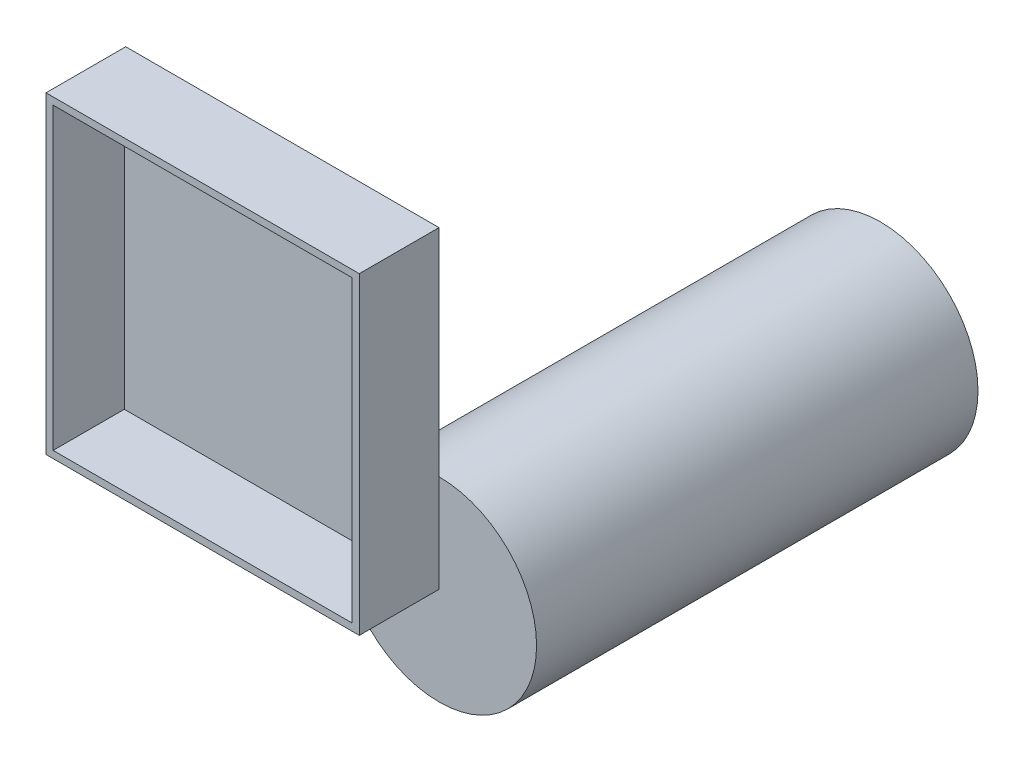
SolidWorks part; units mm, degrees
ref_plane "前基準面" through (0, 0, 0) normal (0, 0, 1) x (1, 0, 0)
ref_plane "上基準面" through (0, 0, 0) normal (0, 1, 0) x (1, 0, 0)
ref_plane "右基準面" through (0, 0, 0) normal (1, 0, 0) x (0, 0, -1)
sketch "草圖1" plane through (0, 0, 0) normal (0, 0, 1) x (1, 0, 0)
  circle A0 centre (0, 0) radius 34.25
  circle A1 centre (0, 0) radius 31.75
  dimension "D1" = 68.5
  dimension "D2" = 63.5
extrude "填料-伸長1" add sketch "草圖1" along normal blind 150
sketch "草圖3" plane through (0, 0, 150) normal (0, 0, 1) x (1, 0, 0)
  circle A0 centre (0, 0) radius 34.25
  dimension "D1" = 68.5
extrude "填料-伸長2" add sketch "草圖3" along normal blind 5
sketch "草圖4" plane through (0, 0, 155) normal (0, 0, 1) x (1, 0, 0)
  line L0 (-55, 110) -> (-55, 51.8909) construction
  line L1 (0, 0) -> (-110, 0)
  line L2 (0, 0) -> (0, 110)
  line L3 (0, 110) -> (-110, 110)
  line L4 (-110, 0) -> (-110, 110)
  dimension "D1" = 110
  dimension "D2" = 110
extrude "填料-伸長3" add sketch "草圖4" along normal blind 3 contours L2 L1 L4 L3
sketch "草圖5" plane through (0, 0, 158) normal (0, 0, 1) x (1, 0, 0)
  line L0 (-55, 110) -> (-55, 55) construction
  line L1 (0, 110) -> (-110, 110) construction
  line L2 (-110, 0) -> (-110, 110) construction
  line L3 (-2.5, 2.5) -> (-107.5, 2.5)
  line L4 (-2.5, 2.5) -> (-2.5, 107.5)
  line L5 (-2.5, 107.5) -> (-107.5, 107.5)
  line L6 (-107.5, 2.5) -> (-107.5, 107.5)
  line L7 (-55, 107.5) -> (-55, 2.5) construction
  line L8 (-2.5, 55) -> (-107.5, 55) construction
  line L9 (-110, 0) -> (0, 0)
  line L11 (0, 0) -> (0, 110)
  line L12 (0, 110) -> (-110, 110)
  line L13 (-110, 0) -> (-110, 110)
  line L14 (-55, 110) -> (-55, -0.9045) construction
  line L15 (0, 55) -> (-110, 55) construction
  dimension "D1" = 2.5
  dimension "D2" = 2.5
extrude "填料-伸長4" add sketch "草圖5" along normal blind 25
